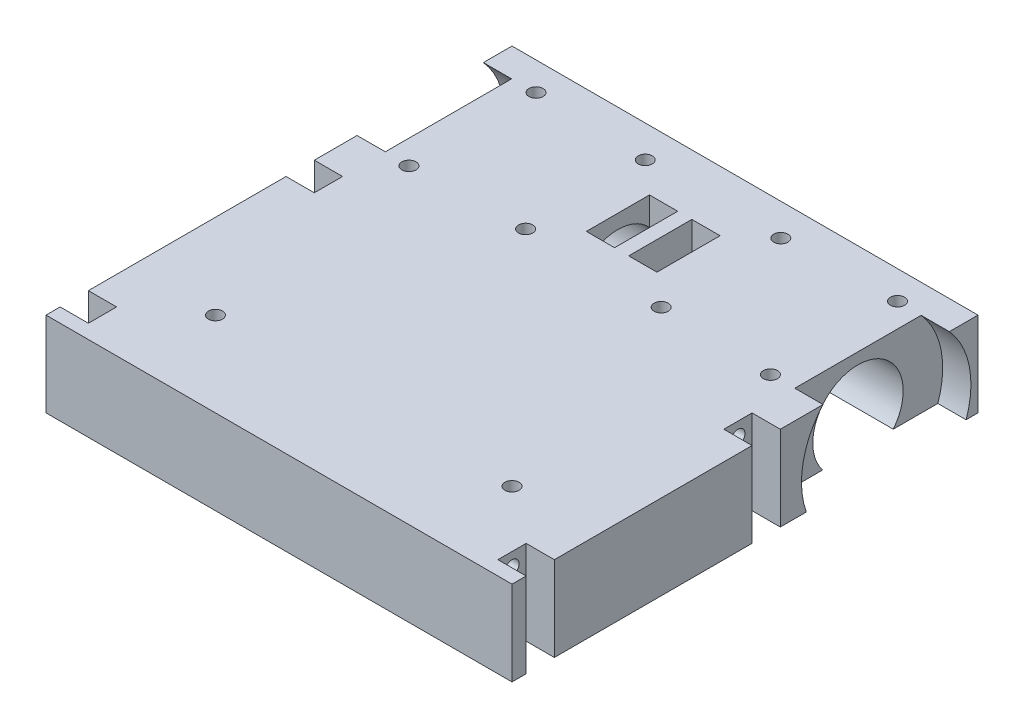
SolidWorks part; units mm, degrees
ref_plane "Plan de face" through (0, 0, 0) normal (0, 0, 1) x (1, 0, 0)
ref_plane "Plan de dessus" through (0, 0, 0) normal (0, 1, 0) x (1, 0, 0)
ref_plane "Plan de droite" through (0, 0, 0) normal (1, 0, 0) x (0, 0, -1)
sketch "Esquisse2" plane through (0, 0, 0) normal (0, 1, 0) x (1, 0, 0)
  line L1 (82.5, 82.5) -> (-82.5, 82.5)
  line L2 (82.5, 82.5) -> (82.5, -82.5)
  line L3 (82.5, -82.5) -> (-82.5, -82.5)
  line L4 (-82.5, 82.5) -> (-82.5, -82.5)
  line L5 (82.5, 82.5) -> (-82.5, -82.5) construction
  line L6 (82.5, -82.5) -> (-82.5, 82.5) construction
  point P0 (0, 0)
  dimension "D1" = 165
  dimension "D2" = 165
extrude "BASE" add sketch "Esquisse2" along normal blind 30
sketch "Esquisse3" plane through (82.5, 0, 0) normal (1, 0, 0) x (0, 0, -1)
  line L0 (82.5, 10) -> (31.0775, 10) construction
  line L1 (82.5, 30) -> (82.5, 0) construction
  line L2 (-82.5, 0) -> (82.5, 0) construction
  circle A0 centre (50, 10) radius 15
  point P4 (50, 10)
  dimension "D3" = 30
  dimension "D1" = 32.5
  dimension "D2" = 10
extrude "BLOC MOTEUR 1." cut sketch "Esquisse3" against normal blind 80
sketch "Esquisse4" plane through (0, 0, 0) normal (0, -1, 0) x (1, 0, 0)
  line L0 (2.5, -61.1803) -> (82.5, -61.1803) construction
  line L1 (2.5, -38.8197) -> (12.5, -38.8197)
  line L2 (2.5, -38.8197) -> (2.5, -61.1803)
  line L3 (2.5, -61.1803) -> (12.5, -61.1803)
  line L4 (12.5, -38.8197) -> (12.5, -61.1803)
  dimension "D1" = 10
extrude "ACCES MOTEUR" cut sketch "Esquisse4" against normal blind 37
ref_plane "PLAN SYM " through (0, 0, 0) normal (1, 0, 0) x (0, 0, -1)
sketch "Esquisse6" plane through (82.5, 0, 0) normal (1, 0, 0) x (0, 0, -1)
  line L0 (35, 10) -> (65, 10) construction
  arc A0 (38.8197, 20) -> (38.8197, 0) centre (50, 10) ccw construction
  arc A1 (61.1803, 0) -> (38.8197, 0) centre (50, 10) ccw construction
  circle A2 centre (50, 10) radius 16.01
  dimension "D1" = 32.02
extrude "BLOC MOTEUR 2" cut sketch "Esquisse6" against normal blind 37
mirror "SYM BLOC MOTEUR" about plane through (0, 0, 0) normal (1, 0, 0) of "ACCES MOTEUR", "BLOC MOTEUR 1.", "BLOC MOTEUR 2"
sketch "Esquisse7" plane through (0, 0, 0) normal (0, -1, 0) x (1, 0, 0)
  line L0 (-64, -37.4972) -> (-64, -72.5028) construction
  line L1 (-82.5, -37.4972) -> (-45.5, -37.4972) construction
  line L2 (-24, -38.8197) -> (-24, -67.469) construction
  line L3 (-45.5, -38.8197) -> (-2.5, -38.8197) construction
  line L4 (-45.5, -62.5028) -> (-82.5, -62.5028) construction
  line L5 (-2.5, -61.1803) -> (-45.5, -61.1803) construction
  line L6 (-64, -37.4972) -> (-64, -13.9891) construction
  line L7 (-24, -71.1803) -> (-24, -20.9291) construction
  circle A0 centre (-64, -27.4972) radius 2.5
  circle A1 centre (-24, -28.8197) radius 2.5
  circle A2 centre (-24, -71.1803) radius 2.5
  circle A3 centre (-64, -72.5028) radius 2.5
  point P8 (-64, -27.4972)
  point P9 (-64, -72.5028)
  point P10 (-24, -71.1803)
  point P11 (-24, -28.8197)
  dimension "D5" = 5
  dimension "D6" = 5
  dimension "D7" = 5
  dimension "D8" = 5
  dimension "D1" = 10
  dimension "D2" = 10
  dimension "D3" = 10
  dimension "D4" = 10
extrude "VIS MOTEUR" cut sketch "Esquisse7" against normal through all
mirror "SYM VIS" about plane through (0, 0, 0) normal (1, 0, 0) of "VIS MOTEUR"
sketch "Esquisse8" plane through (0, 0, 0) normal (0, -1, 0) x (1, 0, 0)
  line L0 (-82.5, 82.5) -> (82.5, 82.5) construction
  line L1 (-82.5, -37.4972) -> (-82.5, 82.5) construction
  line L2 (82.5, 82.5) -> (82.5, -37.4972) construction
  circle A0 centre (-52.5, 52.5) radius 2.5
  circle A1 centre (52.5, 52.5) radius 2.5
  point P0 (-52.5, 52.5)
  point P1 (52.5, 52.5)
  dimension "D5" = 5
  dimension "D6" = 5
  dimension "D1" = 30
  dimension "D2" = 30
  dimension "D3" = 30
  dimension "D4" = 30
extrude "VIS PATIN" cut sketch "Esquisse8" against normal through all
sketch "Esquisse12" plane through (-82.5, 0, 0) normal (-1, 0, 0) x (0, 0, 1)
  circle A0 centre (-50, 10) radius 30
  dimension "D1" = 60
extrude "ESPACE ROUE " cut sketch "Esquisse12" against normal blind 10
mirror "SYM ESPACE ROUE" about plane through (0, 0, 0) normal (1, 0, 0) of "ESPACE ROUE "
sketch "Esquisse23" plane through (82.5, 0, 0) normal (1, 0, 0) x (0, 0, -1)
  line L0 (20.0461, 11.6625) -> (20.0461, -3.5531) construction
  line L1 (-77.5, 30) -> (-67.5, 30)
  line L2 (-77.5, 30) -> (-77.5, 0)
  line L3 (-77.5, 0) -> (-67.5, 0)
  line L4 (-67.5, 30) -> (-67.5, 0)
  line L6 (-82.5, 0) -> (21.7157, 0) construction
  line L8 (-82.5, 30) -> (-82.5, 0) construction
  line L9 (-82.5, 30) -> (27.6393, 30) construction
  line L10 (12.5, 0) -> (2.5, 0)
  line L11 (12.5, 0) -> (12.5, 30)
  line L12 (12.5, 30) -> (2.5, 30)
  line L13 (2.5, 0) -> (2.5, 30)
  arc A1 (27.6393, 30) -> (21.7157, 0) centre (50, 10) ccw construction
  point P19 (7.5, 0)
  dimension "D1" = 5
  dimension "D2" = 10
  dimension "D4" = 10
  dimension "D5" = 90
extrude "VIDE TIGE" cut sketch "Esquisse23" against normal blind 10
mirror "SYM TIGE" about plane through (0, 0, 0) normal (1, 0, 0) of "VIDE TIGE"
sketch "Esquisse25" plane through (72.5, 0, 0) normal (1, 0, 0) x (0, 0, -1)
  line L0 (-77.5, 30) -> (-67.5, 0) construction
  line L1 (-67.5, 0) -> (-72.5, 0) construction
  line L2 (-77.5, 0) -> (-67.5, 0) construction
  line L3 (-72.5, 0) -> (-72.5, 30) construction
  line L4 (-67.5, 30) -> (-77.5, 30) construction
  line L5 (2.5, 30) -> (-67.5, 0) construction
  line L6 (-67.5, 0) -> (-67.5, 30) construction
  line L7 (-67.5, 30) -> (-32.5, 30) construction
  line L8 (-67.5, 30) -> (2.5, 30) construction
  line L9 (-32.5, 30) -> (-32.5, -2.9576) construction
  circle A0 centre (-72.5, 25) radius 2.5
  circle A1 centre (-72.5, 15) radius 2.5
  circle A2 centre (-72.5, 5) radius 2.5
  circle A3 centre (7.5, 5) radius 2.5
  circle A4 centre (7.5, 25) radius 2.5
  circle A5 centre (7.5, 15) radius 2.5
  dimension "D1" = 5
  dimension "D2" = 5
  dimension "D3" = 5
  dimension "D4" = 10
  dimension "D5" = 10
  dimension "D6" = 5
extrude "VIDE VIS" cut sketch "Esquisse25" against normal up to next
ref_plane "Plan5" through (0, 15, 0) normal (0, 1, 0) x (1, 0, 0)
sketch "Esquisse27" plane through (0, 15, 0) normal (0, 1, 0) x (1, 0, 0)
  line L0 (-77.5, -62.5) -> (-77.5, -2.5)
  line L1 (-77.5, -2.5) -> (-68.5, -2.5)
  line L2 (-68.5, -2.5) -> (-68.5, 16.1422)
  line L3 (-68.5, 16.1422) -> (-68.5, 33.4972)
  line L4 (-68.5, 33.4972) -> (-45.5, 33.4972)
  line L5 (-45.5, 33.4972) -> (-45.5, 34.8197)
  line L6 (-45.5, 34.8197) -> (45.5, 34.8197)
  line L7 (0, -77.5) -> (0, 77.5) construction
  line L8 (67.5, -77.5) -> (-67.5, -77.5)
  line L9 (-67.5, -77.5) -> (-67.5, -62.5)
  line L10 (-67.5, -62.5) -> (-77.5, -62.5)
  line L11 (-82.5, -82.5) -> (82.5, -82.5) construction
  line L12 (-72.5, -67.5) -> (-72.5, -77.5) construction
  line L13 (-72.5, -67.5) -> (-82.5, -67.5) construction
  line L14 (-82.5, 2.5) -> (-82.5, -67.5) construction
  line L15 (-72.5, 2.5) -> (-72.5, 12.5) construction
  line L16 (-72.5, 37.4972) -> (-45.5, 37.4972) construction
  line L17 (-45.5, 38.8197) -> (-2.5, 38.8197) construction
  line L18 (-72.5, 62.5028) -> (-72.5, 78.2843) construction
  line L19 (-68.5, 66.5028) -> (-45.5, 66.5028)
  line L20 (-72.5, 2.5) -> (-82.5, 2.5) construction
  line L21 (68.5, 77.5) -> (-68.5, 77.5)
  line L22 (-68.5, 77.5) -> (-68.5, 66.5028)
  line L23 (82.5, 82.5) -> (-82.5, 82.5) construction
  line L24 (-45.5, 62.5028) -> (-72.5, 62.5028) construction
  line L25 (-45.5, 66.5028) -> (-45.5, 65.1803)
  line L26 (-45.5, 65.1803) -> (45.5, 65.1803)
  line L27 (45.5, 66.5028) -> (45.5, 65.1803)
  line L28 (-2.5, 61.1803) -> (-45.5, 61.1803) construction
  line L29 (68.5, 77.5) -> (68.5, 66.5028)
  line L30 (68.5, 66.5028) -> (45.5, 66.5028)
  line L31 (67.5, -62.5) -> (77.5, -62.5)
  line L32 (67.5, -77.5) -> (67.5, -62.5)
  line L33 (45.5, 33.4972) -> (45.5, 34.8197)
  line L34 (68.5, 33.4972) -> (45.5, 33.4972)
  line L35 (68.5, 16.1422) -> (68.5, 33.4972)
  line L36 (68.5, -2.5) -> (68.5, 16.1422)
  line L37 (77.5, -2.5) -> (68.5, -2.5)
  line L38 (77.5, -62.5) -> (77.5, -2.5)
  point P14 (-72.5, -72.5)
  point P48 (0, 65.1803)
  point P49 (0, 34.8197)
  dimension "D1" = 5
  dimension "D2" = 5
  dimension "D3" = 5
  dimension "D4" = 5
  dimension "D5" = 4
  dimension "D6" = 4
  dimension "D7" = 4
  dimension "D8" = 5
  dimension "D9" = 4
  dimension "D10" = 4
  dimension "D11" = 4
  dimension "D12" = 0
  dimension "D13" = 5
extrude "Enlèv. mat.-Extru.1" cut sketch "Esquisse27" against normal blind 10 and the other way blind 10
sketch "Esquisse29" plane through (0, 15, 0) normal (0, 1, 0) x (1, 0, 0)
  line L0 (-82.5, -67.5) -> (82.5, -67.5) construction
  line L2 (82.5, -67.5) -> (-82.5, 2.5) construction
  line L3 (-82.5, 2.5) -> (82.5, 2.5) construction
  line L4 (82.5, 2.5) -> (-82.5, -67.5) construction
  line L5 (-76.0988, 2.5) -> (0, -29.7843)
  line L6 (82.5, -67.5) -> (82.5, 2.5) construction
  line L7 (-82.5, -0.2157) -> (-6.4012, -32.5)
  line L8 (-82.5, 2.5) -> (-82.5, -67.5) construction
  line L10 (0, -32.5) -> (0, -67.5) construction
  line L11 (76.0988, 2.5) -> (0, -29.7843)
  line L12 (82.5, -0.2157) -> (6.4012, -32.5)
  line L13 (0, -35.2157) -> (76.0988, -67.5)
  line L14 (6.4012, -32.5) -> (50.3886, -51.1613)
  line L15 (-6.4012, -32.5) -> (-50.3886, -51.1613)
  line L16 (0, -35.2157) -> (-76.0988, -67.5)
  line L17 (-82.5, -64.7843) -> (-82.5, -67.5)
  line L18 (-82.5, -67.5) -> (-76.0988, -67.5)
  line L19 (76.0988, -67.5) -> (82.5, -67.5)
  line L20 (82.5, -67.5) -> (82.5, -64.7843)
  line L21 (76.0988, 2.5) -> (82.5, 2.5)
  line L22 (82.5, 2.5) -> (82.5, -0.2157)
  line L23 (-76.0988, 2.5) -> (-82.5, 2.5)
  line L24 (-82.5, 2.5) -> (-82.5, -0.2157)
  line L25 (-54.9299, -53.0879) -> (-82.5, -64.7843)
  line L26 (54.9299, -53.0879) -> (82.5, -64.7843)
  arc A0 (50.3886, -51.1613) -> (54.9299, -53.0879) centre (52.5, -52.5) ccw
  arc A1 (-54.9299, -53.0879) -> (-50.3886, -51.1613) centre (-52.5, -52.5) ccw
  point P4 (0, -32.5)
  dimension "D1" = 2.5
  dimension "D2" = 2.5
extrude "Boss.-Extru.1" add sketch "Esquisse29" along normal blind 2.5 and the other way blind 2.5
